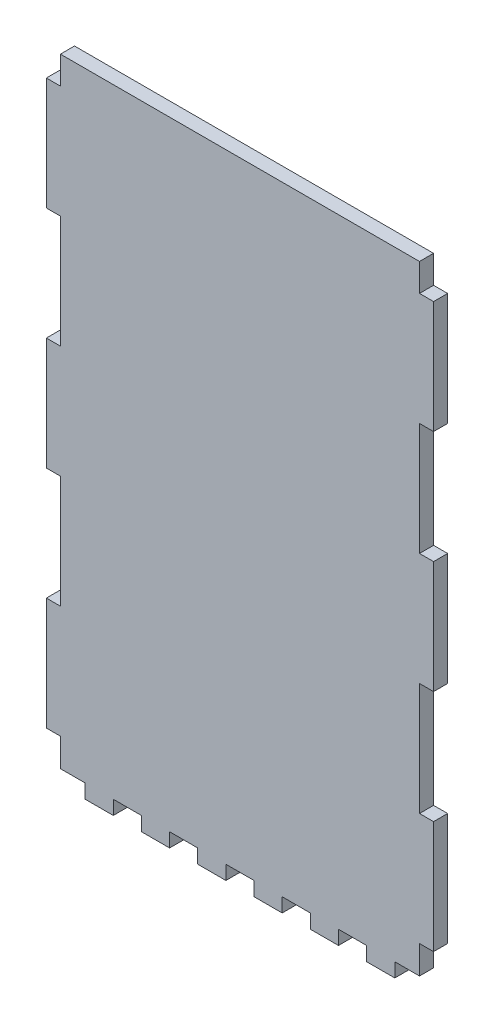
SolidWorks part; units mm, degrees
material "Acrylic (Medium-high impact)"
ref_plane "Front Plane" through (0, 0, 0) normal (0, 0, 1) x (1, 0, 0)
ref_plane "Top Plane" through (0, 0, 0) normal (0, 1, 0) x (1, 0, 0)
ref_plane "Right Plane" through (0, 0, 0) normal (1, 0, 0) x (0, 0, -1)
sketch "Sketch1" plane through (0, 0, 0) normal (0, 0, 1) x (1, 0, 0)
  line L0 (0, 3.175) -> (5.575, 3.175)
  line L1 (5.575, 3.175) -> (5.575, 0)
  line L2 (5.575, 0) -> (11.925, 0)
  line L3 (11.925, 0) -> (11.925, 3.175)
  line L4 (11.925, 3.175) -> (18.275, 3.175)
  line L5 (18.275, 3.175) -> (18.275, 0)
  line L6 (18.275, 0) -> (24.625, 0)
  line L7 (0, 3.175) -> (0, 9.525)
  line L8 (24.625, 0) -> (24.625, 3.175)
  line L9 (24.625, 3.175) -> (30.975, 3.175)
  line L10 (30.975, 3.175) -> (30.975, 0)
  line L11 (30.975, 0) -> (37.325, 0)
  line L12 (37.325, 0) -> (37.325, 3.175)
  line L13 (37.325, 3.175) -> (43.675, 3.175)
  line L14 (40.5, -1047.625) -> (40.5, 48952.375) construction
  line L15 (0, 142.775) -> (81, 142.775)
  line L16 (43.675, 0) -> (43.675, 3.175)
  line L17 (50.025, 0) -> (43.675, 0)
  line L18 (50.025, 3.175) -> (50.025, 0)
  line L19 (56.375, 3.175) -> (50.025, 3.175)
  line L20 (56.375, 0) -> (56.375, 3.175)
  line L21 (81, 142.775) -> (81, 136.525)
  line L22 (62.725, 0) -> (56.375, 0)
  line L23 (62.725, 3.175) -> (62.725, 0)
  line L24 (69.075, 3.175) -> (62.725, 3.175)
  line L25 (69.075, 0) -> (69.075, 3.175)
  line L26 (75.425, 0) -> (69.075, 0)
  line L27 (75.425, 3.175) -> (75.425, 0)
  line L28 (81, 3.175) -> (75.425, 3.175)
  line L29 (0, 9.525) -> (-3.175, 9.525)
  line L30 (-3.175, 9.525) -> (-3.175, 34.925)
  line L31 (-3.175, 34.925) -> (0, 34.925)
  line L32 (0, 60.325) -> (-3.175, 60.325)
  line L33 (-3.175, 60.325) -> (-3.175, 85.725)
  line L34 (-3.175, 85.725) -> (0, 85.725)
  line L35 (81, 9.525) -> (84.175, 9.525)
  line L36 (84.175, 9.525) -> (84.175, 34.925)
  line L37 (84.175, 34.925) -> (81, 34.925)
  line L38 (81, 60.325) -> (84.175, 60.325)
  line L39 (84.175, 85.725) -> (81, 85.725)
  line L40 (84.175, 60.325) -> (84.175, 85.725)
  line L41 (0, 85.725) -> (0, 111.125)
  line L42 (0, 34.925) -> (0, 60.325)
  line L43 (81, 9.525) -> (81, 3.175)
  line L44 (81, 60.325) -> (81, 34.925)
  line L45 (0, 111.125) -> (-3.175, 111.125)
  line L46 (-3.175, 111.125) -> (-3.175, 136.525)
  line L47 (-3.175, 136.525) -> (0, 136.525)
  line L48 (0, 136.525) -> (0, 142.775)
  line L49 (84.175, 136.525) -> (81, 136.525)
  line L50 (81, 111.125) -> (84.175, 111.125)
  line L51 (84.175, 111.125) -> (84.175, 136.525)
  line L52 (81, 111.125) -> (81, 85.725)
  point P21 (40.5, 3.175)
  dimension "D1" = 3.175
  dimension "D2" = 6.35
  dimension "D3" = 3.175
  dimension "D5" = 3.175
  dimension "D6" = 139.6
  dimension "D7" = 81
  dimension "D8" = 6.35
  dimension "D10" = 25.4
  dimension "D9" = 25.4
extrude "Boss-Extrude1" add sketch "Sketch1" along normal blind 3.175
